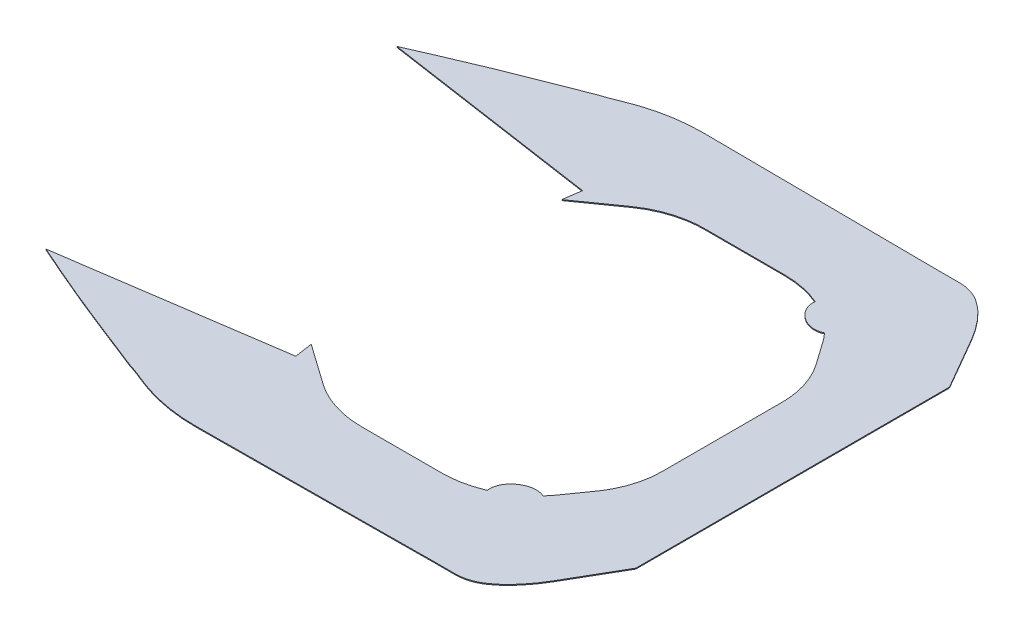
SolidWorks part; units mm, degrees
ref_plane "前视基准面" through (0, 0, 0) normal (0, 0, 1) x (1, 0, 0)
ref_plane "上视基准面" through (0, 0, 0) normal (0, 1, 0) x (1, 0, 0)
ref_plane "右视基准面" through (0, 0, 0) normal (1, 0, 0) x (0, 0, -1)
sketch "草图1" plane through (0, -10.9491, 0) normal (0, 1, 0) x (1, 0, 0)
  line L21 (-67.0451, -117.9838) -> (-76.0782, -117.9838)
  line L22 (-82.3669, -116.006) -> (-86.9679, -112.7595)
  line L23 (-86.9679, -112.7595) -> (-86.667, -114.8078)
  line L24 (-86.667, -114.8078) -> (-111.2417, -118.4258)
  line L25 (-111.2417, -118.4258) -> (-108.0967, -119.8008)
  line L26 (-85.4029, -127.2762) -> (-58.7812, -127.0794)
  line L27 (-58.7812, -127.0794) -> (-56.4307, -127.0794)
  line L28 (-50.1853, -122.2572) -> (-46.751, -116.323)
  line L29 (-46.751, -116.323) -> (-46.7506, -80.91)
  line L30 (-46.7506, -80.91) -> (-50.1849, -74.9758)
  line L31 (-56.4301, -70.1535) -> (-58.7806, -70.1534)
  line L32 (-58.7806, -70.1534) -> (-85.4024, -69.9561)
  line L33 (-108.0963, -77.431) -> (-111.2413, -78.806)
  line L34 (-111.2413, -78.806) -> (-86.6667, -82.4245)
  line L35 (-86.6667, -82.4245) -> (-86.9677, -84.4727)
  line L36 (-86.9677, -84.4727) -> (-82.3666, -81.2264)
  line L37 (-76.0778, -79.2487) -> (-67.0447, -79.2489)
  line L38 (-58.2697, -83.7066) -> (-56.5166, -86.1912)
  line L39 (-54.7117, -91.8337) -> (-54.7119, -98.6164)
  line L40 (-54.7119, -98.6164) -> (-54.7119, -105.3992)
  line L41 (-56.5169, -111.0416) -> (-58.27, -113.5263)
  line L42 (-67.0451, -117.9838) -> (-76.0782, -117.9838)
  line L43 (-82.3669, -116.006) -> (-86.9679, -112.7595)
  line L44 (-86.9679, -112.7595) -> (-86.667, -114.8078)
  line L45 (-86.667, -114.8078) -> (-111.2417, -118.4258)
  line L46 (-111.2417, -118.4258) -> (-108.0967, -119.8008)
  line L47 (-85.4029, -127.2762) -> (-58.7812, -127.0794)
  line L48 (-58.7812, -127.0794) -> (-56.4307, -127.0794)
  line L49 (-50.1853, -122.2572) -> (-46.751, -116.323)
  line L50 (-46.751, -116.323) -> (-46.7506, -80.91)
  line L51 (-46.7506, -80.91) -> (-50.1849, -74.9758)
  line L52 (-56.4301, -70.1535) -> (-58.7806, -70.1534)
  line L53 (-58.7806, -70.1534) -> (-85.4024, -69.9561)
  line L54 (-108.0963, -77.431) -> (-111.2413, -78.806)
  line L55 (-111.2413, -78.806) -> (-86.6667, -82.4245)
  line L56 (-86.6667, -82.4245) -> (-86.9677, -84.4727)
  line L57 (-86.9677, -84.4727) -> (-82.3666, -81.2264)
  line L58 (-76.0778, -79.2487) -> (-67.0447, -79.2489)
  line L59 (-58.2697, -83.7066) -> (-56.5166, -86.1912)
  line L60 (-54.7117, -91.8337) -> (-54.7119, -98.6164)
  line L61 (-54.7119, -98.6164) -> (-54.7119, -105.3992)
  line L62 (-56.5169, -111.0416) -> (-58.27, -113.5263)
  arc A0 (-62.6862, -80.2114) -> (-59.2121, -82.7192) centre (-60.0973, -80.2851) ccw construction
  arc A1 (-59.1666, -114.463) -> (-62.7491, -117.0492) centre (-60.0977, -116.9476) ccw construction
  arc A8 (-62.7459, -117.1123) -> (-59.0573, -114.5068) centre (-60.0977, -116.9476) ccw
  arc A9 (-93.3198, -125.6983) -> (-95.1968, -125.0109) centre (-101.1572, -144.1925) ccw
  arc A10 (-93.3198, -125.6983) -> (-85.4029, -127.2762) centre (-85.5501, -107.3639) ccw
  arc A11 (-56.4307, -127.0794) -> (-53.8907, -126.3732) centre (-56.428, -122.1679) ccw
  arc A12 (-53.8907, -126.3732) -> (-52.5325, -125.3176) centre (-62.3232, -114.1216) ccw
  arc A13 (-52.5325, -125.3176) -> (-50.1853, -122.2572) centre (-63.0987, -114.7837) ccw
  arc A14 (-50.1849, -74.9758) -> (-52.5319, -71.9153) centre (-63.0983, -82.449) ccw
  arc A15 (-52.5319, -71.9153) -> (-53.8902, -70.8597) centre (-62.3229, -83.1111) ccw
  arc A16 (-53.8902, -70.8597) -> (-56.4301, -70.1535) centre (-56.4275, -75.065) ccw
  arc A17 (-85.4024, -69.9561) -> (-93.3193, -71.5338) centre (-85.5499, -89.8684) ccw
  arc A18 (-95.1963, -72.2212) -> (-93.3193, -71.5338) centre (-101.1563, -53.0395) ccw
  arc A19 (-59.1024, -82.6764) -> (-62.6836, -80.1469) centre (-60.0973, -80.2851) ccw
  arc A21 (-93.3198, -125.6983) -> (-95.1968, -125.0109) centre (-101.1572, -144.1925) ccw
  arc A22 (-93.3198, -125.6983) -> (-85.4029, -127.2762) centre (-85.5501, -107.3639) ccw
  arc A23 (-56.4307, -127.0794) -> (-53.8907, -126.3732) centre (-56.428, -122.1679) ccw
  arc A24 (-53.8907, -126.3732) -> (-52.5325, -125.3176) centre (-62.3232, -114.1216) ccw
  arc A25 (-52.5325, -125.3176) -> (-50.1853, -122.2572) centre (-63.0987, -114.7837) ccw
  arc A26 (-50.1849, -74.9758) -> (-52.5319, -71.9153) centre (-63.0983, -82.449) ccw
  arc A27 (-52.5319, -71.9153) -> (-53.8902, -70.8597) centre (-62.3229, -83.1111) ccw
  arc A28 (-53.8902, -70.8597) -> (-56.4301, -70.1535) centre (-56.4275, -75.065) ccw
  arc A29 (-85.4024, -69.9561) -> (-93.3193, -71.5338) centre (-85.5499, -89.8684) ccw
  arc A30 (-95.1963, -72.2212) -> (-93.3193, -71.5338) centre (-101.1563, -53.0395) ccw
  ellipse E8 centre (-67.0451, -107.8838) end of major axis (-77.6252, -107.8837) minor radius 10.1 (-67.0451, -117.9838) -> (-62.7459, -117.1123) ccw
  ellipse E9 centre (-76.0782, -107.8838) end of major axis (-65.4981, -107.8839) minor radius 10.1 (-82.3669, -116.006) -> (-76.0782, -117.9838) ccw
  ellipse E10 centre (-76.078, -89.3487) end of major axis (-65.4979, -89.3488) minor radius 10.1 (-76.0778, -79.2487) -> (-82.3666, -81.2264) ccw
  ellipse E11 centre (-67.0449, -89.3489) end of major axis (-56.4648, -89.349) minor radius 10.1 (-62.6836, -80.1469) -> (-67.0447, -79.2489) ccw
  ellipse E12 centre (-67.0449, -89.3489) end of major axis (-56.4648, -89.349) minor radius 10.1 (-58.2697, -83.7066) -> (-59.1024, -82.6764) ccw
  ellipse E13 centre (-65.2918, -91.8335) end of major axis (-54.7117, -91.8336) minor radius 10.1 (-54.7117, -91.8337) -> (-56.5166, -86.1912) ccw
  ellipse E14 centre (-65.292, -105.3992) end of major axis (-75.8721, -105.3991) minor radius 10.1 (-56.5169, -111.0416) -> (-54.7119, -105.3992) ccw
  ellipse E15 centre (-67.0451, -107.8838) end of major axis (-77.6252, -107.8837) minor radius 10.1 (-59.0573, -114.5068) -> (-58.27, -113.5263) ccw
  ellipse E16 centre (-67.0451, -107.8838) end of major axis (-77.6252, -107.8837) minor radius 10.1 (-67.0451, -117.9838) -> (-62.7459, -117.1123) ccw
  ellipse E17 centre (-76.0782, -107.8838) end of major axis (-65.4981, -107.8839) minor radius 10.1 (-82.3669, -116.006) -> (-76.0782, -117.9838) ccw
  ellipse E18 centre (-76.078, -89.3487) end of major axis (-65.4979, -89.3488) minor radius 10.1 (-76.0778, -79.2487) -> (-82.3666, -81.2264) ccw
  ellipse E19 centre (-67.0449, -89.3489) end of major axis (-56.4648, -89.349) minor radius 10.1 (-62.6836, -80.1469) -> (-67.0447, -79.2489) ccw
  ellipse E20 centre (-67.0449, -89.3489) end of major axis (-56.4648, -89.349) minor radius 10.1 (-58.2697, -83.7066) -> (-59.1024, -82.6764) ccw
  ellipse E21 centre (-65.2918, -91.8335) end of major axis (-54.7117, -91.8336) minor radius 10.1 (-54.7117, -91.8337) -> (-56.5166, -86.1912) ccw
  ellipse E22 centre (-65.292, -105.3992) end of major axis (-75.8721, -105.3991) minor radius 10.1 (-56.5169, -111.0416) -> (-54.7119, -105.3992) ccw
  ellipse E23 centre (-67.0451, -107.8838) end of major axis (-77.6252, -107.8837) minor radius 10.1 (-59.0573, -114.5068) -> (-58.27, -113.5263) ccw
  spline S0 degree 3 poles (-62.6836, -80.1469) (-62.8944, -81.8963) (-60.688, -83.4733) (-59.1024, -82.6764) knots 0 0 0 0 1 1 1 1
  spline S1 degree 3 poles (-59.0573, -114.5068) (-60.6733, -113.7141) (-63.016, -115.2434) (-62.7459, -117.1123) knots 0 0 0 0 1 1 1 1
  spline S6 degree 3 poles (706.7645, 2755.775) (-293.5217, 37.269) (-212.4871, -78.4459) (-100.5952, -122.8974) (-99.515, -123.3188) (-38.5027, -147.056) (23.8074, -164.3125) (-1011.3594, -2977.9455) knots -25.209337 -25.209337 -25.209337 -25.209337 0.5 0.5 0.75 0.75 14.615595 14.615595 14.615595 14.615595 only from (-108.0967, -119.8008) to (-95.1968, -125.0109)
  spline S7 degree 3 poles (-1011.3203, 2780.7796) (23.8094, -32.9217) (-38.5014, -50.1771) (-99.5145, -73.9132) (-100.5947, -74.3346) (-212.4871, -118.7838) (-293.5239, -234.4965) (706.6988, -2952.9974) knots -13.615674 -13.615674 -13.615674 -13.615674 0.25 0.25 0.5 0.5 26.209257 26.209257 26.209257 26.209257 only from (-95.1963, -72.2212) to (-108.0963, -77.431)
  spline S8 degree 3 poles (-108.0967, -119.8008) (-105.9718, -120.7299) (-103.8279, -121.6132) (-100.5952, -122.8974) (-99.515, -123.3188) (-97.3538, -124.1596) (-96.2725, -124.578) (-95.1968, -125.0109) knots 0 0 0 0 0.5 0.5 0.75 0.75 1 1 1 1
  spline S9 degree 3 poles (-95.1963, -72.2212) (-96.272, -72.654) (-97.3533, -73.0725) (-99.5145, -73.9132) (-100.5947, -74.3346) (-103.8275, -75.6188) (-105.9714, -76.502) (-108.0963, -77.431) knots 0 0 0 0 0.25 0.25 0.5 0.5 1 1 1 1
  dimension "D1" = 0
extrude "凸台-拉伸1" add sketch "草图1" along normal blind 0.1
